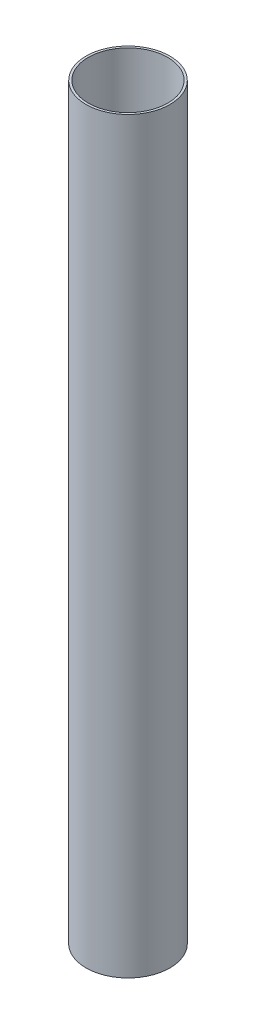
SolidWorks part; units mm, degrees
ref_plane "Front Plane" through (0, 0, 0) normal (0, 0, 1) x (1, 0, 0)
ref_plane "Top Plane" through (0, 0, 0) normal (0, 1, 0) x (1, 0, 0)
ref_plane "Right Plane" through (0, 0, 0) normal (1, 0, 0) x (0, 0, -1)
sketch "Sketch1" plane through (0, 0, 0) normal (0, 0, 1) x (1, 0, 0)
  line L0 (26.9748, 0) -> (28.4988, 0)
  line L1 (28.4988, 0) -> (28.4988, 508)
  line L2 (28.4988, 508) -> (26.9748, 508)
  line L7 (26.9748, 0) -> (26.9748, 508)
  point P0 (0, 0)
  dimension "D1" = 26.9748
  dimension "D2" = 1.524
  dimension "D3" = 508
ref_axis "Central Axis" through (0, 123.6201, 0) along (0, -1, 0)
revolve "Revolve1" add sketch "Sketch1" angle 360 about axis through (0, 123.6201, 0) along (0, -1, 0)
